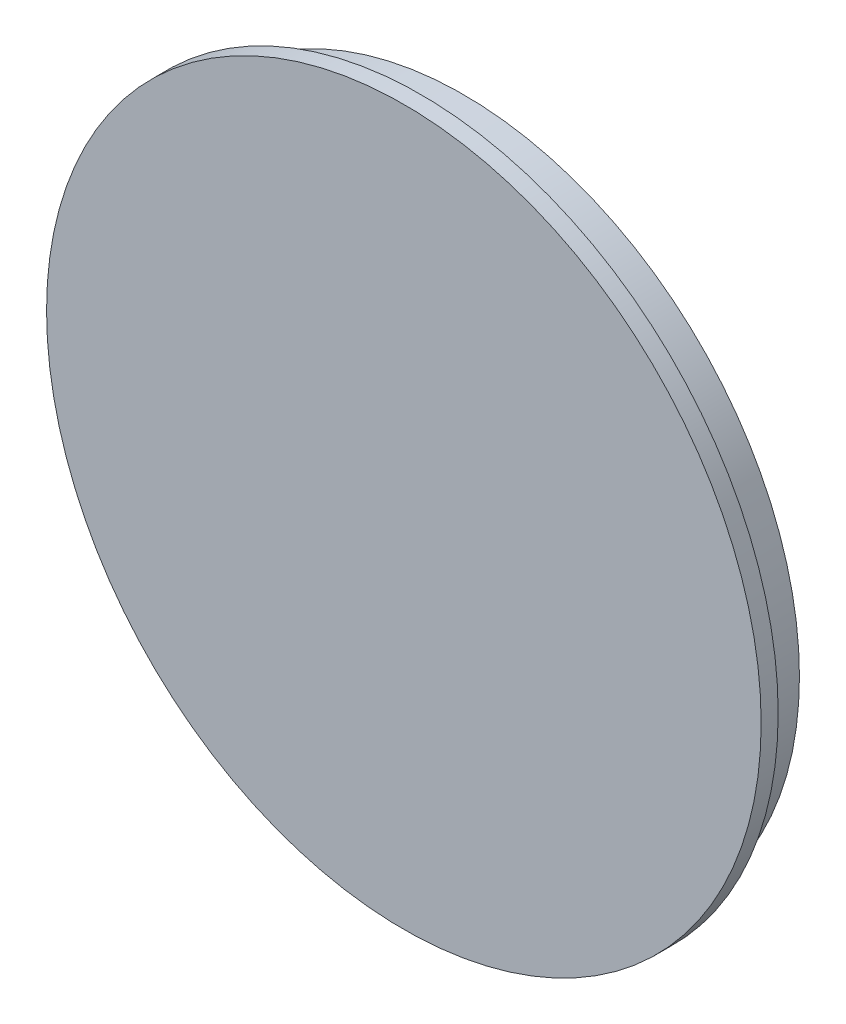
SolidWorks part; units mm, degrees
ref_plane "Front Plane" through (0, 0, 0) normal (0, 0, 1) x (1, 0, 0)
ref_plane "Top Plane" through (0, 0, 0) normal (0, 1, 0) x (1, 0, 0)
ref_plane "Right Plane" through (0, 0, 0) normal (1, 0, 0) x (0, 0, -1)
sketch "Sketch1" plane through (0, 0, 0) normal (0, 0, 1) x (1, 0, 0)
  circle A0 centre (0, 0) radius 39.5
  circle A1 centre (0, 0) radius 37.5
  dimension "D1" = 79
  dimension "D2" = 2
extrude "Boss-Extrude1" add sketch "Sketch1" along normal blind 5
sketch "Sketch2" plane through (0, 0, 5) normal (0, 0, 1) x (1, 0, 0)
  circle A0 centre (0, 0) radius 42
  dimension "D1" = 84
extrude "Boss-Extrude2" add sketch "Sketch2" along normal blind 2
fillet "Fillet1" radius 2 1 edges at (37.5, 0, 5)
